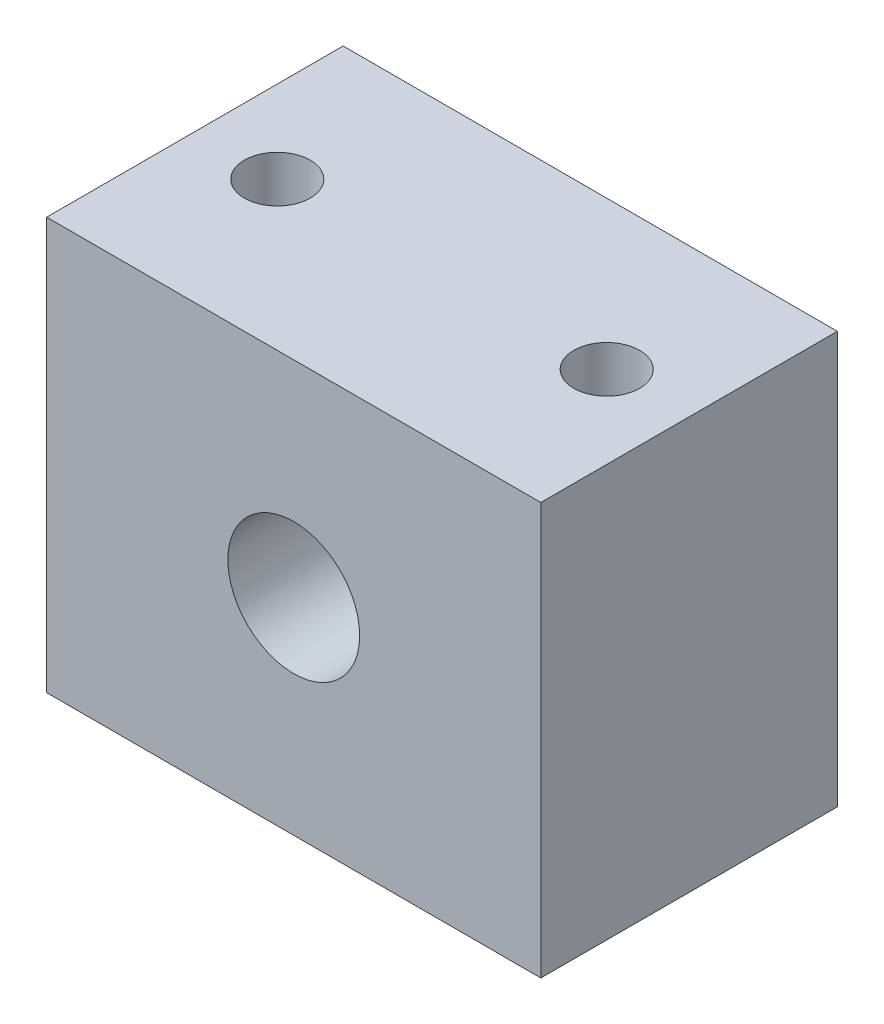
SolidWorks part; units mm, degrees
ref_plane "Front Plane" through (0, 0, 0) normal (0, 0, 1) x (1, 0, 0)
ref_plane "Top Plane" through (0, 0, 0) normal (0, 1, 0) x (1, 0, 0)
ref_plane "Right Plane" through (0, 0, 0) normal (1, 0, 0) x (0, 0, -1)
sketch "Sketch1" plane through (0, 0, 0) normal (0, 0, 1) x (1, 0, 0)
  line L1 (-15, 12.5) -> (15, 12.5)
  line L2 (-15, 12.5) -> (-15, -12.5)
  line L3 (-15, -12.5) -> (15, -12.5)
  line L4 (15, 12.5) -> (15, -12.5)
  line L5 (-15, 12.5) -> (15, -12.5) construction
  line L6 (-15, -12.5) -> (15, 12.5) construction
  circle A0 centre (0, 0) radius 4
  dimension "D1" = 8
  dimension "D2" = 25
  dimension "D3" = 30
extrude "Boss-Extrude1" add sketch "Sketch1" along normal blind 18
sketch "Sketch3" plane through (0, 12.5, 0) normal (0, 1, 0) x (1, 0, 0)
  line L0 (0, -1000) -> (0, 49000) construction
  line L1 (-1020, -9) -> (48980, -9) construction
  line L2 (-15, -18) -> (-15, 0) construction
  circle A0 centre (-10, -9) radius 2
  circle A1 centre (10, -9) radius 2
  point P8 (-15, -9)
  dimension "D2" = 4
  dimension "D1" = 5
extrude "Cut-Extrude1" cut sketch "Sketch3" against normal through all
